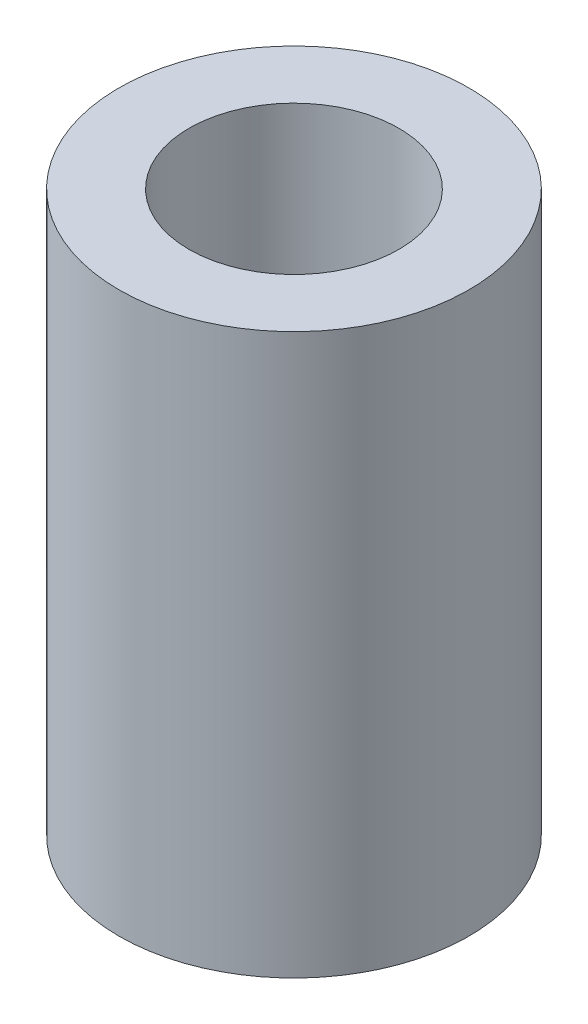
SolidWorks part; units mm, degrees
ref_plane "前视基准面" through (0, 0, 0) normal (0, 0, 1) x (1, 0, 0)
ref_plane "上视基准面" through (0, 0, 0) normal (0, 1, 0) x (1, 0, 0)
ref_plane "右视基准面" through (0, 0, 0) normal (1, 0, 0) x (0, 0, -1)
sketch "草图1" plane through (0, 0, 0) normal (0, 1, 0) x (1, 0, 0)
  circle A0 centre (0, 0) radius 2.5
  circle A1 centre (0, 0) radius 1.5
  dimension "D1" = 3
  dimension "D2" = 5
extrude "凸台-拉伸1" add sketch "草图1" along normal blind 8
